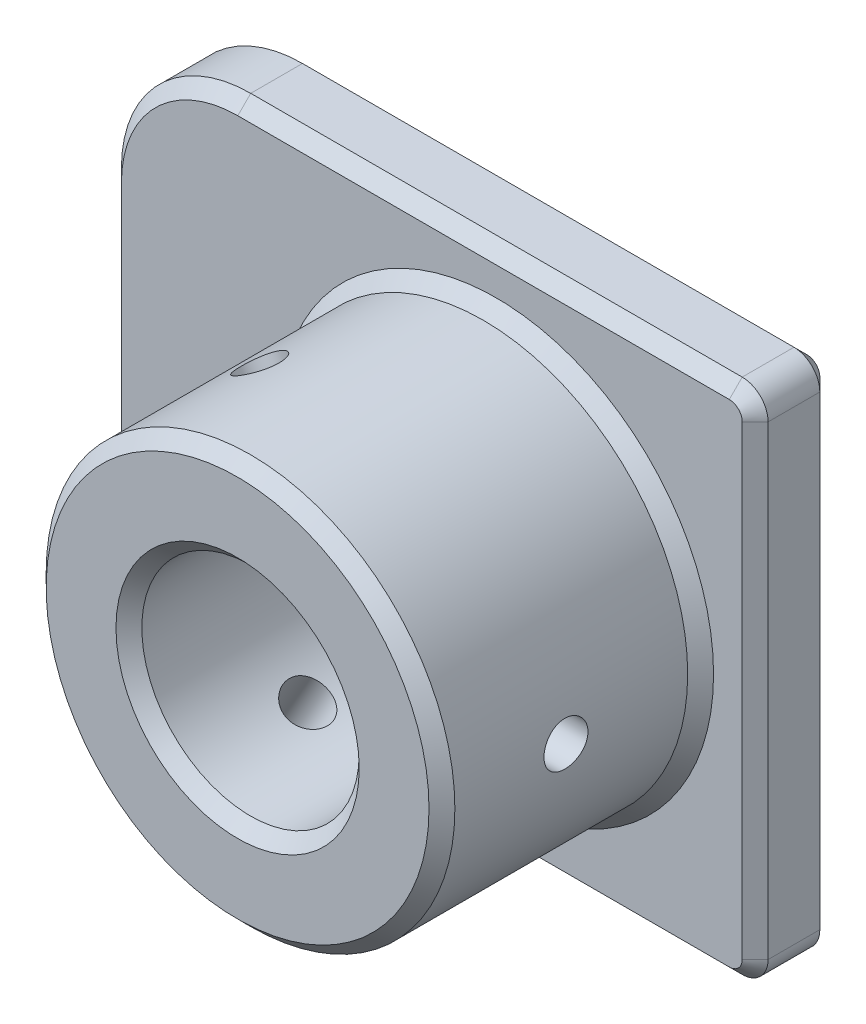
SolidWorks part; units mm, degrees
ref_plane "Front Plane" through (0, 0, 0) normal (0, 0, 1) x (1, 0, 0)
ref_plane "Top Plane" through (0, 0, 0) normal (0, 1, 0) x (1, 0, 0)
ref_plane "Right Plane" through (0, 0, 0) normal (1, 0, 0) x (0, 0, -1)
other "Graphic1"
other "Graphic (Closed) -1"
sketch "Sketch1" plane through (0, 0, 0) normal (0, 0, 1) x (1, 0, 0)
  line L0 (-0.01, -0.0358) -> (0.0182, -0.0358) construction
  line L2 (0.009, -0.0258) -> (-0.01, -0.0258)
  line L3 (0.01, -0.0268) -> (0.01, -0.0448)
  line L4 (0.009, -0.0458) -> (-0.01, -0.0458)
  line L5 (-0.015, -0.0308) -> (-0.015, -0.0408)
  circle A0 centre (0, -0.0358) radius 0.005
  circle A1 centre (0, -0.0358) radius 0.0079
  arc A2 (-0.01, -0.0258) -> (-0.015, -0.0308) centre (-0.01, -0.0308) ccw
  arc A3 (-0.01, -0.0458) -> (-0.015, -0.0408) centre (-0.01, -0.0408) cw
  arc A4 (0.01, -0.0448) -> (0.009, -0.0458) centre (0.009, -0.0448) cw
  arc A5 (0.009, -0.0258) -> (0.01, -0.0268) centre (0.009, -0.0268) cw
  point P9 (0, 0)
  point P14 (-0.015, -0.0458)
  point P17 (0.01, -0.0458)
  dimension "D4" = 0.005
  dimension "D5" = 0.001
  dimension "D6" = 0.0158
  dimension "D7" = 0.01
  dimension "D1" = 0.01
  dimension "D2" = 0.01
  dimension "D3" = 0.025
extrude "Boss-Extrude1" add sketch "Sketch1" along normal blind 0.003
sketch "Sketch2" plane through (0, 0, 0.003) normal (0, 0, 1) x (1, 0, 0)
  circle A0 centre (0, -0.0358) radius 0.0079
  circle A1 centre (0, -0.0358) radius 0.0042
extrude "Boss-Extrude3" add sketch "Sketch2" along normal blind 0.01
chamfer "Chamfer1" distance 0.0005 angle 45 20 edges at (-0.0005, -0.0458, 0) (-0.0005, -0.0458, 0.003) (-0.0135, -0.0443, 0) (-0.0135, -0.0443, 0.003) (-0.015, -0.0358, 0) (-0.015, -0.0358, 0.003) (-0.0135, -0.0273, 0) (-0.0135, -0.0273, 0.003) (-0.0005, -0.0258, 0) (-0.0005, -0.0258, 0.003) (0.0097, -0.0261, 0) (0.0097, -0.0261, 0.003) (0.01, -0.0358, 0) (0.01, -0.0358, 0.003) (0.0097, -0.0455, 0) (0.0097, -0.0455, 0.003) (0.0079, -0.0358, 0.013) (0.0079, -0.0358, 0.003) (0.0042, -0.0358, 0.013) (0.005, -0.0358, 0)
sketch "Sketch3" plane through (0.01, 0, 0) normal (1, 0, 0) x (0, 0, -1)
  line L1 (0, -0.0279) -> (0, -0.0437) construction
  line L2 (0, -0.0358) -> (-0.0191, -0.0358) construction
  circle A0 centre (-0.0082, -0.0358) radius 0.0009
  point P2 (0, 0)
  dimension "D1" = 0.0017
extrude "Cut-Extrude1" cut sketch "Sketch3" against normal up to next and the other way through all
pattern_circular "CirPattern1" count 3 over 360 about axis through (0, -0.0358, 0.0125) along (0, 0, 1) of "Cut-Extrude1"
scale "Scale1" bodies to scale 105 scale about centroid uniform scaling yes scale factor 1000
